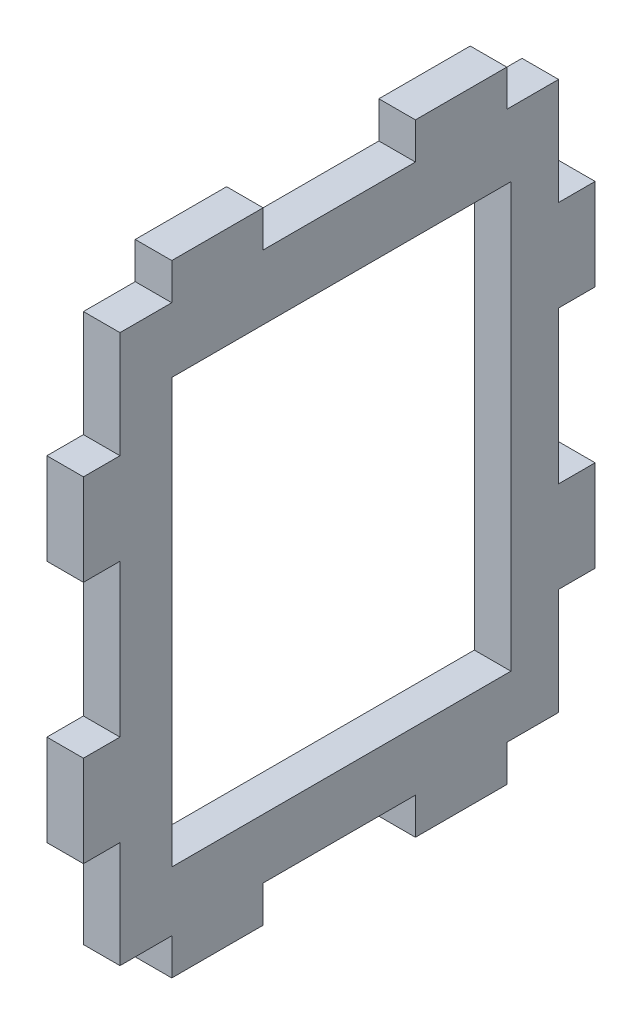
SolidWorks part; units mm, degrees
ref_plane "Front Plane" through (0, 0, 0) normal (0, 0, 1) x (1, 0, 0)
ref_plane "Top Plane" through (0, 0, 0) normal (0, 1, 0) x (1, 0, 0)
ref_plane "Right Plane" through (0, 0, 0) normal (1, 0, 0) x (0, 0, -1)
sketch "Sketch1" plane through (0, 0, 0) normal (1, 0, 0) x (0, 0, -1)
  line L0 (0, 0) -> (0, 23.6997) construction
  line L1 (36, -45) -> (27.5, -45)
  line L2 (36, -45) -> (36, -27.5)
  line L3 (36, 45) -> (27.5, 45)
  line L4 (-36, -45) -> (-36, -27.5)
  line L5 (36, -45) -> (-36, 45) construction
  line L6 (36, 45) -> (-36, -45) construction
  line L7 (0, 0) -> (23.6746, 0) construction
  line L8 (12.5, 45) -> (12.5, 51)
  line L9 (36, 27.5) -> (42, 27.5)
  line L11 (36, 12.5) -> (42, 12.5)
  line L12 (42, 27.5) -> (42, 12.5)
  line L14 (-27.5, 45) -> (-27.5, 51)
  line L15 (-27.5, 51) -> (-12.5, 51)
  line L16 (-12.5, 45) -> (-12.5, 51)
  line L17 (27.5, 51) -> (12.5, 51)
  line L18 (27.5, 45) -> (27.5, 51)
  line L21 (27.5, -45) -> (27.5, -51)
  line L22 (27.5, -51) -> (12.5, -51)
  line L23 (-12.5, -45) -> (-12.5, -51)
  line L24 (-27.5, -51) -> (-12.5, -51)
  line L25 (-27.5, -45) -> (-27.5, -51)
  line L27 (12.5, -45) -> (12.5, -51)
  line L28 (42, -27.5) -> (42, -12.5)
  line L29 (36, -12.5) -> (42, -12.5)
  line L31 (36, -27.5) -> (42, -27.5)
  line L32 (-36, 12.5) -> (-42, 12.5)
  line L33 (-42, 27.5) -> (-42, 12.5)
  line L34 (-36, 27.5) -> (-42, 27.5)
  line L35 (-36, -27.5) -> (-42, -27.5)
  line L36 (-42, -27.5) -> (-42, -12.5)
  line L37 (-36, -12.5) -> (-42, -12.5)
  line L38 (-36, 27.5) -> (-36, 45)
  line L39 (-36, -12.5) -> (-36, 12.5)
  line L40 (36, -12.5) -> (36, 12.5)
  line L41 (36, 27.5) -> (36, 45)
  line L42 (12.5, 45) -> (-12.5, 45)
  line L43 (-27.5, 45) -> (-36, 45)
  line L44 (12.5, -45) -> (-12.5, -45)
  line L45 (-27.5, -45) -> (-36, -45)
  line L47 (-27.5, 34.375) -> (28.1754, 34.375)
  line L48 (-27.5, 34.375) -> (-27.5, -35.2192)
  line L49 (-27.5, -35.2192) -> (28.1754, -35.2192)
  line L50 (28.1754, 34.375) -> (28.1754, -35.2192)
  point P0 (0, 0)
  point P14 (42, 20)
  point P19 (-20, 51)
  dimension "D1" = 90
  dimension "D2" = 72
  dimension "D3" = 20
  dimension "D4" = 6
  dimension "D5" = 15
  dimension "D6" = 20
  dimension "D7" = 15
  dimension "D8" = 6
extrude "Boss-Extrude1" add sketch "Sketch1" along normal blind 6
